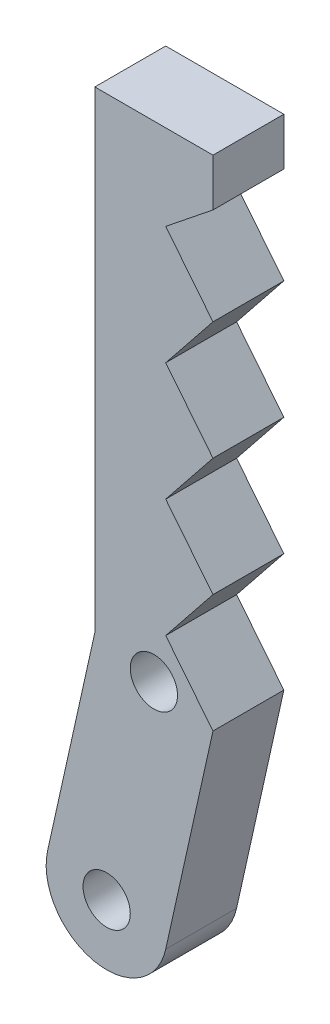
SolidWorks part; units mm, degrees
ref_plane "Front Plane" through (0, 0, 0) normal (0, 0, 1) x (1, 0, 0)
ref_plane "Top Plane" through (0, 0, 0) normal (0, 1, 0) x (1, 0, 0)
ref_plane "Right Plane" through (0, 0, 0) normal (1, 0, 0) x (0, 0, -1)
sketch "Sketch1" plane through (0, 0, 0) normal (0, 0, 1) x (1, 0, 0)
  line L0 (-10, 40.1279) -> (-10, 0.1279)
  line L1 (-10, 0.1279) -> (-14.0006, -17.8729)
  line L2 (0, 40.1279) -> (0, -46.6607) construction
  line L5 (-10, 0.1279) -> (0, -2.0945) construction
  line L6 (0, -2.0945) -> (-4, 2.9055)
  line L7 (-4, 2.9055) -> (0, 7.9055)
  line L8 (0, 7.9055) -> (-4, 12.9055)
  line L9 (-4, 12.9055) -> (0, 17.9055)
  line L10 (0, 17.9055) -> (-4, 22.9055)
  line L11 (-4, 22.9055) -> (0, 27.9055)
  line L12 (0, 27.9055) -> (-4, 32.9055)
  line L13 (-4, 32.9055) -> (0, 36.1055)
  line L14 (0, 36.1055) -> (0, 40.1279)
  line L15 (0, 40.1279) -> (-10, 40.1279)
  line L16 (-4, 46.089) -> (-4, -39.042) construction
  line L18 (0, -2.0945) -> (-4, -20.0927)
  circle A5 centre (-5, -0.9833) radius 2
  arc A6 (-14.0006, -17.8729) -> (-4, -20.0927) centre (-9, -18.9815) ccw
  circle A7 centre (-9, -18.9815) radius 2
  point P21 (0, 0)
  point P22 (0, 0)
  point P23 (-4, 22.8781)
  point P24 (0, 0)
  dimension "D7" = 4
  dimension "D8" = 4
  dimension "D6" = 18.4374
  dimension "D2" = 10
  dimension "D3" = 90
  dimension "D4" = 40
  dimension "D5" = 18.44
  dimension "D9" = 5
  dimension "D10" = 5
  dimension "D11" = 167.47
  dimension "D12" = 5
  dimension "D13" = 5
  dimension "D14" = 5
  dimension "D15" = 5
  dimension "D16" = 5
extrude "Boss-Extrude1" add sketch "Sketch1" along normal blind 6
